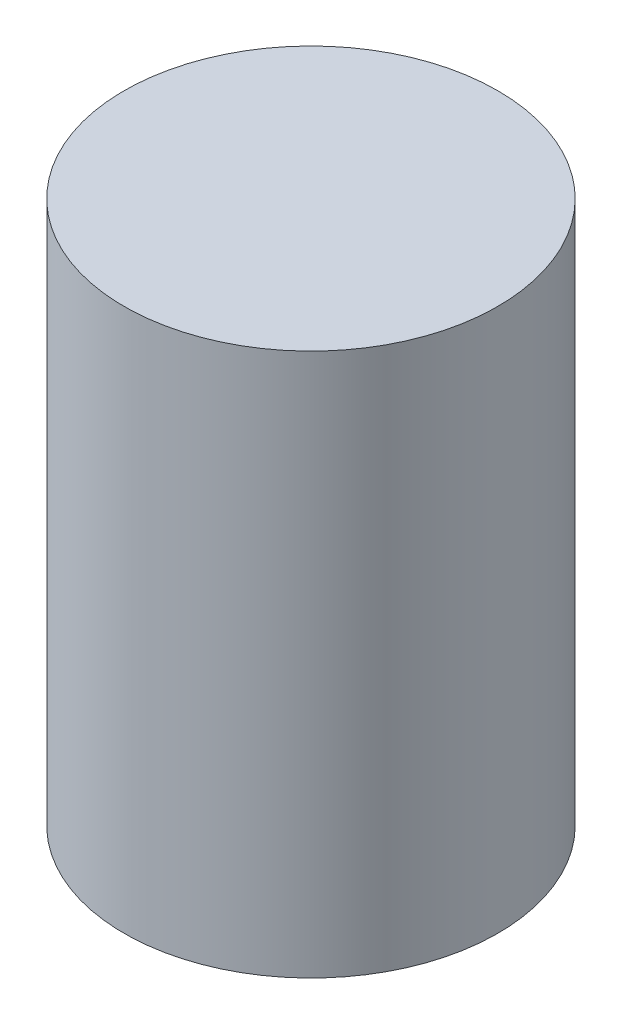
SolidWorks part; units mm, degrees
ref_plane "Front Plane" through (0, 0, 0) normal (0, 0, 1) x (1, 0, 0)
ref_plane "Top Plane" through (0, 0, 0) normal (0, 1, 0) x (1, 0, 0)
ref_plane "Right Plane" through (0, 0, 0) normal (1, 0, 0) x (0, 0, -1)
sketch "Sketch1" plane through (0, 0, 0) normal (0, 1, 0) x (1, 0, 0)
  circle A0 centre (0, 0) radius 15.9
  dimension "D1" = 31.8
extrude "Boss-Extrude1" add sketch "Sketch1" along normal blind 46.2 contours A0
ref_plane "Plane1" through (0, 0, 50.8) normal (0, 0, 1) x (1, 0, 0)
sketch "Sketch3" plane through (0, 0, 50.8) normal (0, 0, 1) x (1, 0, 0)
  line L0 (-27.686, 23.1) -> (27.686, 23.1) construction
  line L1 (0, 23.1) -> (0, 0) construction
  line L3 (-15.9, 46.2) -> (-15.9, 23.1) construction
  line L4 (-15.9, 46.2) -> (-15.9, 0) construction
  line L5 (-15.9, 23.1) -> (-15.9, 0) construction
  line L6 (15.9, 46.2) -> (15.9, 23.1) construction
  line L7 (15.9, 0) -> (15.9, 46.2) construction
  line L8 (15.9, 23.1) -> (15.9, 0) construction
  line L9 (15.9, 0) -> (-15.9, 0) construction
  text T0 "LI-COR LI-192\r\nUnderwater PAR Sensor" font "Adobe Gothic Std B" height in points 8
  dimension "D1" = 55.372
